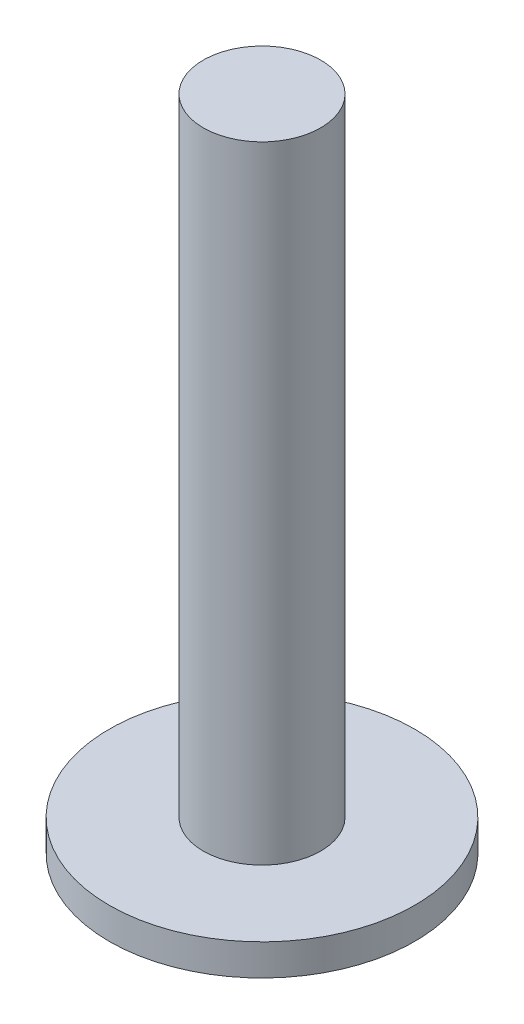
SolidWorks part; units mm, degrees
ref_plane "前视基准面" through (0, 0, 0) normal (0, 0, 1) x (1, 0, 0)
ref_plane "上视基准面" through (0, 0, 0) normal (0, 1, 0) x (1, 0, 0)
ref_plane "右视基准面" through (0, 0, 0) normal (1, 0, 0) x (0, 0, -1)
other "Configuration Table"
sketch "草图1" plane through (0, 0, 0) normal (0, 1, 0) x (1, 0, 0)
  line L0 (0, 0) -> (-50000, 0) construction
  line L1 (0, 0) -> (0, 50000) construction
  line L2 (-1, 0) -> (-1, 0.2)
  line L3 (-1, 0.2) -> (-0.2, 0.2)
  line L4 (-0.2, 0.2) -> (-0.2, 1)
  line L5 (-0.2, 1) -> (0, 1)
  line L6 (0, 1) -> (0.2, 1)
  line L7 (0.2, 1) -> (0.2, 0.2)
  line L8 (0.2, 0.2) -> (1, 0.2)
  line L9 (1, 0.2) -> (1, 0)
  line L10 (1, 0) -> (1, -0.2)
  line L11 (1, -0.2) -> (0.2, -0.2)
  line L12 (0.2, -0.2) -> (0.2, -1)
  line L13 (0.2, -1) -> (0, -1)
  line L14 (0, -1) -> (-0.2, -1)
  line L15 (-0.2, -1) -> (-0.2, -0.2)
  line L16 (-0.2, -0.2) -> (-1, -0.2)
  line L17 (-1, -0.2) -> (-1, 0)
  circle A0 centre (0, 0) radius 3.9
  point P30 (0, 0)
  dimension "D1" = 7.8
  dimension "D2" = 0.2
  dimension "D5" = 0.8
  dimension "D6" = 4
extrude "凸台-拉伸1" add sketch "草图1" along normal blind 0.8
sketch "草图2" plane through (0, 0.8, 0) normal (0, 1, 0) x (1, 0, 0)
  circle A0 centre (0, 0) radius 1.5
  dimension "D1" = 3
extrude "凸台-拉伸4" add sketch "草图2" along normal blind 16
